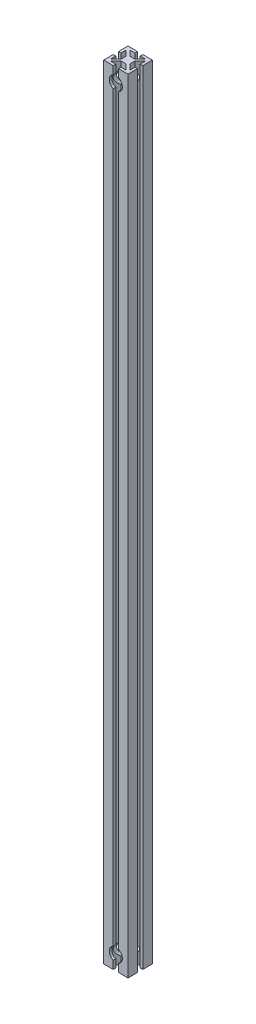
SolidWorks part; units mm, degrees
ref_plane "Front Plane" through (0, 0, 0) normal (0, 0, 1) x (1, 0, 0)
ref_plane "Top Plane" through (0, 0, 0) normal (0, 1, 0) x (1, 0, 0)
ref_plane "Right Plane" through (0, 0, 0) normal (1, 0, 0) x (0, 0, -1)
sketch "Sketch2" plane through (0.5947, 0, 0.5947) normal (0, 1, 0) x (1, 0, 0)
  line L0 (-0.5947, 0.5947) -> (-0.5947, 20.2394) construction
  line L1 (-0.5947, 0.5947) -> (-20.2394, 0.5947) construction
  line L2 (-0.5947, 0.5947) -> (-20.2394, 20.2394) construction
  line L3 (-19.6447, 19.6447) -> (-4.6587, 19.6447)
  line L4 (-4.6587, 19.6447) -> (-4.6587, 15.5807)
  line L5 (-4.6587, 15.5807) -> (-12.707, 15.5807)
  line L6 (-12.707, 15.5807) -> (-4.4774, 7.3511)
  line L7 (-4.4774, 7.3511) -> (3.288, 7.3511)
  line L8 (-19.6447, 19.6447) -> (-19.6447, 4.6587)
  line L9 (-19.6447, 4.6587) -> (-15.5807, 4.6587)
  line L10 (-15.5807, 4.6587) -> (-15.5807, 12.707)
  line L11 (-15.5807, 12.707) -> (-7.3511, 4.4774)
  line L12 (-7.3511, 4.4774) -> (-7.3511, -3.288)
  line L13 (-4.4774, -6.1617) -> (3.288, -6.1617)
  line L14 (-12.707, -14.3913) -> (-4.4774, -6.1617)
  line L15 (-4.6587, -14.3913) -> (-12.707, -14.3913)
  line L16 (-4.6587, -18.4553) -> (-4.6587, -14.3913)
  line L17 (-19.6447, -18.4553) -> (-4.6587, -18.4553)
  line L18 (-19.6447, -18.4553) -> (-19.6447, -3.4693)
  line L19 (-19.6447, -3.4693) -> (-15.5807, -3.4693)
  line L20 (-15.5807, -3.4693) -> (-15.5807, -11.5176)
  line L21 (-15.5807, -11.5176) -> (-7.3511, -3.288)
  line L22 (11.5176, 15.5807) -> (3.288, 7.3511)
  line L23 (3.4693, 15.5807) -> (11.5176, 15.5807)
  line L24 (3.4693, 19.6447) -> (3.4693, 15.5807)
  line L25 (18.4553, 19.6447) -> (3.4693, 19.6447)
  line L26 (18.4553, 19.6447) -> (18.4553, 4.6587)
  line L27 (18.4553, 4.6587) -> (14.3913, 4.6587)
  line L28 (14.3913, 4.6587) -> (14.3913, 12.707)
  line L29 (14.3913, 12.707) -> (6.1617, 4.4774)
  line L30 (6.1617, 4.4774) -> (6.1617, -3.288)
  line L31 (14.3913, -11.5176) -> (6.1617, -3.288)
  line L32 (14.3913, -3.4693) -> (14.3913, -11.5176)
  line L33 (18.4553, -3.4693) -> (14.3913, -3.4693)
  line L34 (18.4553, -18.4553) -> (18.4553, -3.4693)
  line L35 (18.4553, -18.4553) -> (3.4693, -18.4553)
  line L36 (3.4693, -18.4553) -> (3.4693, -14.3913)
  line L37 (3.4693, -14.3913) -> (11.5176, -14.3913)
  line L38 (11.5176, -14.3913) -> (3.288, -6.1617)
  point P26 (-7.3511, 0.5947)
  point P27 (-0.5947, 7.3511)
  point P44 (-0.5947, -6.1617)
  dimension "D1" = 38.1
  dimension "D2" = 8.128
  dimension "D3" = 13.5128
  dimension "D4" = 4.064
  dimension "D5" = 4.064
extrude "Boss-Extrude1" add sketch "Sketch2" along normal up to surface (1223.9625 mm away)
other "1515<1>"
ref_plane "midplane" through (0, 611.9812, 0) normal (0, 1, 0) x (-1, 0, 0)
sketch "Sketch3" plane through (0, 0, 19.05) normal (0, 0, 1) x (1, 0, 0)
  line L0 (-19.05, 0) -> (-4.064, 0) construction
  circle A0 centre (0, 21.844) radius 10.287
  dimension "D1" = 20.574
  dimension "D2" = 21.844
extrude "Cut-Extrude1" cut sketch "Sketch3" against normal blind 16.51
mirror "Mirror1" about plane through (0, 0, 0) normal (0, 0, 1) of "Cut-Extrude1"
mirror "Mirror2" about plane through (0, 611.9812, 0) normal (0, 1, 0) of "Mirror1", "Cut-Extrude1"
